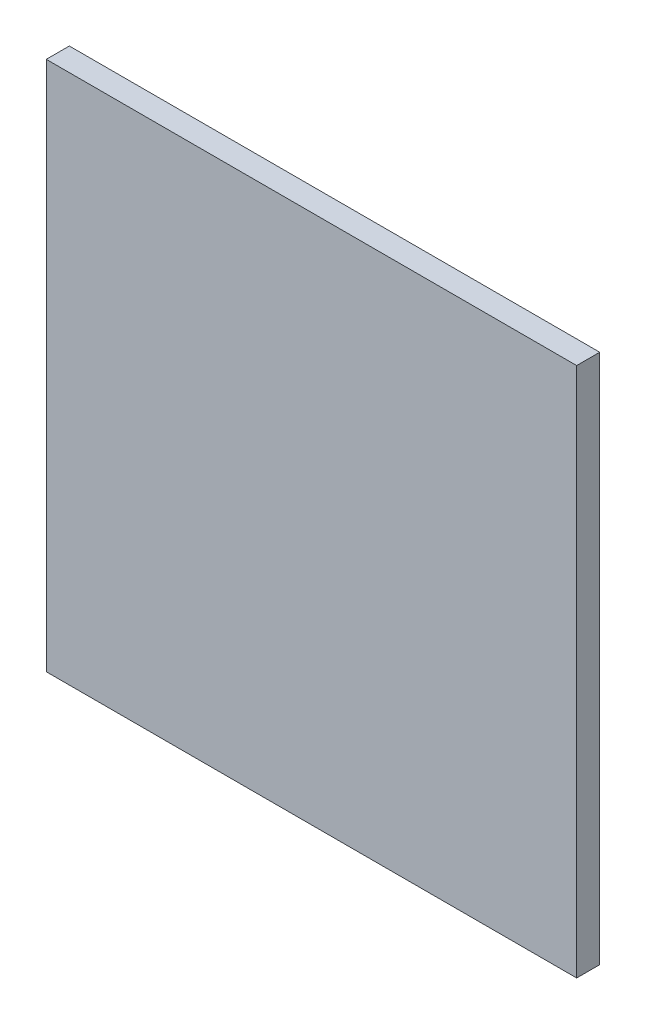
SolidWorks part; units mm, degrees
ref_plane "Front Plane" through (0, 0, 0) normal (0, 0, 1) x (1, 0, 0)
ref_plane "Top Plane" through (0, 0, 0) normal (0, 1, 0) x (1, 0, 0)
ref_plane "Right Plane" through (0, 0, 0) normal (1, 0, 0) x (0, 0, -1)
sketch "Sketch1" plane through (0, 0, 0) normal (0, 0, 1) x (1, 0, 0)
  line L1 (0, 0) -> (460, 0)
  line L2 (0, 0) -> (0, -460)
  line L3 (0, -460) -> (460, -460)
  line L4 (460, 0) -> (460, -460)
  dimension "D1" = 460
  dimension "D2" = 460
extrude "Boss-Extrude1" add sketch "Sketch1" along normal blind 20
